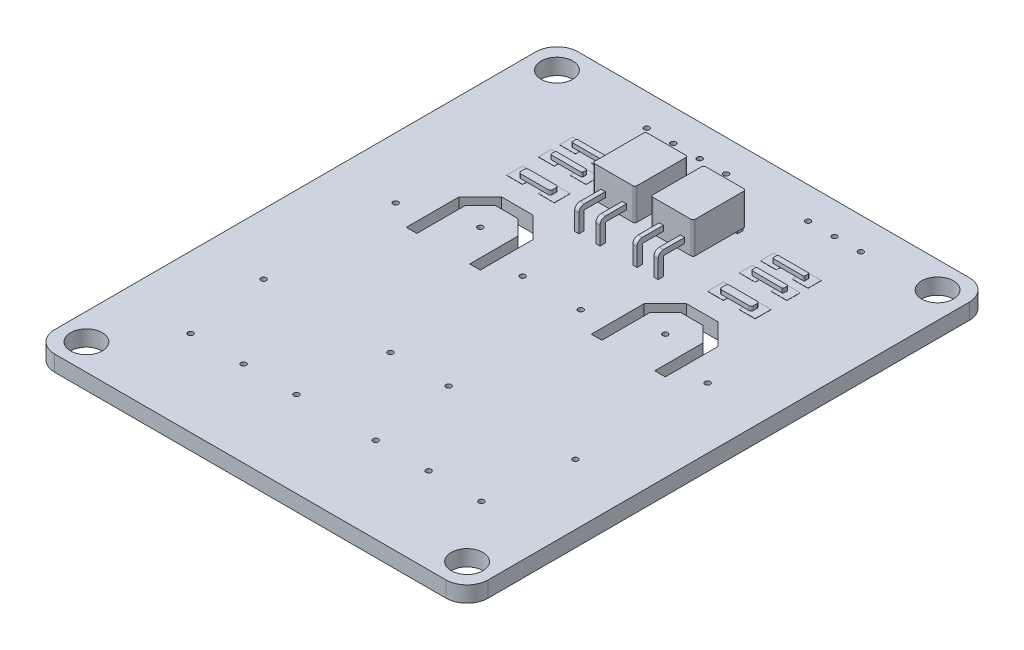
SolidWorks part; units mm, degrees
ref_plane "Ön Düzlem" through (0, 0, 0) normal (0, 0, 1) x (1, 0, 0)
ref_plane "Üst Düzlem" through (0, 0, 0) normal (0, 1, 0) x (1, 0, 0)
ref_plane "Sağ Düzlem" through (0, 0, 0) normal (1, 0, 0) x (0, 0, -1)
sketch "Çizim1" plane through (0, 0, 0) normal (0, 1, 0) x (1, 0, 0)
  line L0 (0, 0) -> (0, 24.75) construction
  line L1 (-18.5, 24.75) -> (18.5, 24.75)
  line L2 (-20.5, 22.75) -> (-20.5, -22.75)
  line L3 (-18.5, -24.75) -> (18.5, -24.75)
  line L4 (20.5, 22.75) -> (20.5, -22.75)
  line L5 (-20.5, 24.75) -> (20.5, -24.75) construction
  line L6 (-20.5, -24.75) -> (20.5, 24.75) construction
  line L7 (0, 24.75) -> (0, 0) construction
  line L8 (0, 0) -> (20.5, 0) construction
  line L9 (-14.75, 24.75) -> (-14.75, -24.75) construction
  line L10 (-20.5, -8.75) -> (20.5, -8.75) construction
  line L11 (-20.5, 3.75) -> (20.5, 3.75) construction
  line L12 (-2.75, 24.75) -> (-2.75, -24.75) construction
  line L13 (-20.5, 5.75) -> (20.5, 5.75) construction
  line L14 (-8.75, 5.75) -> (-8.75, -24.75) construction
  line L15 (-20.5, -16.64) -> (20.5, -16.64) construction
  line L16 (-12.25, 7.25) -> (-10.25, 9.25)
  line L17 (-10.25, 9.25) -> (-7.25, 9.25)
  line L18 (-12.25, 7.25) -> (-12.25, 2.25)
  line L20 (-5.25, 7.25) -> (-5.25, 2.25)
  line L21 (-12.25, 9.25) -> (-5.25, 2.25) construction
  line L22 (-12.25, 2.25) -> (-5.25, 9.25) construction
  line L24 (-6.25, 6.8358) -> (-6.25, 2.25)
  line L26 (-9.8358, 8.25) -> (-7.6642, 8.25)
  line L27 (-11.25, 6.8358) -> (-9.8358, 8.25)
  line L28 (-11.25, 6.8358) -> (-11.25, 2.25)
  line L30 (-12.25, 2.25) -> (-11.25, 2.25)
  line L31 (-6.25, 2.25) -> (-5.25, 2.25)
  line L32 (-7.25, 9.25) -> (-5.25, 7.25)
  line L33 (-7.6642, 8.25) -> (-6.25, 6.8358) construction
  line L34 (-7.25, 9.25) -> (-5.25, 7.25) construction
  line L35 (-7.6642, 8.25) -> (-6.25, 6.8358)
  line L36 (6.25, 2.25) -> (5.25, 2.25)
  line L37 (5.25, 7.25) -> (5.25, 2.25)
  line L38 (6.25, 6.8358) -> (6.25, 2.25)
  line L39 (7.6642, 8.25) -> (6.25, 6.8358)
  line L40 (7.25, 9.25) -> (5.25, 7.25)
  line L41 (9.8358, 8.25) -> (7.6642, 8.25)
  line L42 (10.25, 9.25) -> (7.25, 9.25)
  line L43 (11.25, 6.8358) -> (9.8358, 8.25)
  line L44 (12.25, 7.25) -> (10.25, 9.25)
  line L45 (11.25, 6.8358) -> (11.25, 2.25)
  line L46 (12.25, 7.25) -> (12.25, 2.25)
  line L47 (12.25, 2.25) -> (11.25, 2.25)
  line L48 (-20.5, 21.75) -> (20.5, 21.75) construction
  line L49 (8.75, 5.75) -> (8.75, 24.75) construction
  arc A0 (18.5, -24.75) -> (20.5, -22.75) centre (18.5, -22.75) ccw
  arc A1 (-20.5, -22.75) -> (-18.5, -24.75) centre (-18.5, -22.75) ccw
  arc A2 (18.5, 24.75) -> (20.5, 22.75) centre (18.5, 22.75) cw
  arc A3 (-18.5, 24.75) -> (-20.5, 22.75) centre (-18.5, 22.75) ccw
  circle A4 centre (-18, 22.25) radius 1.5
  circle A5 centre (18, 22.25) radius 1.5
  circle A6 centre (18, -22.25) radius 1.5
  circle A7 centre (-18, -22.25) radius 1.5
  circle A8 centre (-14.75, -8.75) radius 0.25
  circle A10 centre (-2.75, -8.75) radius 0.25
  circle A11 centre (-14.75, 3.75) radius 0.25
  circle A12 centre (-8.75, 5.75) radius 0.25
  circle A13 centre (-2.75, 3.75) radius 0.25
  circle A14 centre (14.75, 3.75) radius 0.25
  circle A15 centre (8.75, 5.75) radius 0.25
  circle A16 centre (2.75, 3.75) radius 0.25
  circle A17 centre (2.75, -8.75) radius 0.25
  circle A18 centre (14.75, -8.75) radius 0.25
  circle A19 centre (-8.75, -16.64) radius 0.25
  circle A20 centre (-3.75, -16.64) radius 0.25
  circle A21 centre (-13.75, -16.64) radius 0.25
  circle A22 centre (3.75, -16.64) radius 0.25
  circle A23 centre (8.75, -16.64) radius 0.25
  circle A24 centre (13.75, -16.64) radius 0.25
  circle A25 centre (-1.5, 21.75) radius 0.25
  circle A26 centre (-4, 21.75) radius 0.25
  circle A27 centre (-6.5, 21.75) radius 0.25
  circle A28 centre (-9, 21.75) radius 0.25
  circle A29 centre (8.75, 21.75) radius 0.25
  circle A30 centre (11.25, 21.75) radius 0.25
  circle A31 centre (6.25, 21.75) radius 0.25
  point P0 (0, 0)
  dimension "D3" = 2
  dimension "D4" = 3
  dimension "D6" = 2.5
  dimension "D9" = 0.5
  dimension "D15" = 0.5
  dimension "D16" = 5
  dimension "D17" = 5
  dimension "D24" = 0.5
  dimension "D25" = 1.5
  dimension "D26" = 2.5
  dimension "D27" = 2.5
  dimension "D28" = 2.5
  dimension "D29" = 0.5
  dimension "D30" = 2.5
  dimension "D31" = 2.5
  dimension "D1" = 41
  dimension "D2" = 49.5
  dimension "D5" = 2.5
  dimension "D7" = 5.75
  dimension "D8" = 16
  dimension "D10" = 12.5
  dimension "D11" = 12
  dimension "D12" = 2
  dimension "D13" = 6
  dimension "D14" = 8.11
  dimension "D18" = 7
  dimension "D19" = 7
  dimension "D21" = 3
  dimension "D20" = 1
extrude "Yükseklik-Ekstrüzyon1" add sketch "Çizim1" along normal blind 1.5
sketch "Çizim2" plane through (0, 1.5, 0) normal (0, 1, 0) x (1, 0, 0)
  line L0 (0, 0) -> (0, 24.75) construction
  line L1 (18.5, 24.75) -> (-18.5, 24.75) construction
  line L2 (-8.75, 9.25) -> (-8.75, 24.75) construction
  line L3 (-7.25, 9.25) -> (-10.25, 9.25) construction
  line L4 (-8.75, 11.25) -> (-20.5, 11.25) construction
  line L5 (-20.5, 22.75) -> (-20.5, -22.75) construction
  line L6 (-8.75, 14.25) -> (-20.5, 14.25) construction
  line L7 (-20.5, 16.25) -> (-8.75, 16.25) construction
  line L8 (-10.25, 9.25) -> (-10.25, 16.25) construction
  line L9 (8.75, 12.75) -> (7.25, 12.75)
  line L10 (-8.75, 11.25) -> (-7.25, 11.25)
  line L11 (-8.75, 11.25) -> (-8.75, 12.75)
  line L12 (-8.75, 12.75) -> (-7.25, 12.75)
  line L13 (-7.25, 11.25) -> (-7.25, 12.75)
  line L14 (-10.25, 11.25) -> (-11.75, 11.25)
  line L15 (-10.25, 11.25) -> (-10.25, 12.75)
  line L16 (-10.25, 12.75) -> (-11.75, 12.75)
  line L17 (-11.75, 11.25) -> (-11.75, 12.75)
  line L18 (-8.75, 14.25) -> (-7.25, 14.25)
  line L19 (-8.75, 14.25) -> (-8.75, 15.5)
  line L20 (-8.75, 15.5) -> (-7.25, 15.5)
  line L21 (-7.25, 14.25) -> (-7.25, 15.5)
  line L22 (-10.25, 14.25) -> (-11.75, 14.25)
  line L23 (-10.25, 14.25) -> (-10.25, 15.5)
  line L24 (-10.25, 15.5) -> (-11.75, 15.5)
  line L25 (-11.75, 14.25) -> (-11.75, 15.5)
  line L26 (-8.75, 16.25) -> (-7.25, 16.25)
  line L27 (-8.75, 16.25) -> (-8.75, 17.5)
  line L28 (-8.75, 17.5) -> (-7.25, 17.5)
  line L29 (-7.25, 16.25) -> (-7.25, 17.5)
  line L30 (-10.25, 16.25) -> (-11.75, 16.25)
  line L31 (-10.25, 16.25) -> (-10.25, 17.5)
  line L32 (-10.25, 17.5) -> (-11.75, 17.5)
  line L33 (-11.75, 16.25) -> (-11.75, 17.5)
  line L34 (7.25, 11.25) -> (7.25, 12.75)
  line L35 (8.75, 11.25) -> (7.25, 11.25)
  line L36 (8.75, 11.25) -> (8.75, 12.75)
  line L37 (10.25, 12.75) -> (11.75, 12.75)
  line L38 (11.75, 11.25) -> (11.75, 12.75)
  line L39 (10.25, 11.25) -> (11.75, 11.25)
  line L40 (10.25, 11.25) -> (10.25, 12.75)
  line L41 (8.75, 15.5) -> (7.25, 15.5)
  line L42 (7.25, 14.25) -> (7.25, 15.5)
  line L43 (8.75, 14.25) -> (7.25, 14.25)
  line L44 (8.75, 14.25) -> (8.75, 15.5)
  line L45 (10.25, 15.5) -> (11.75, 15.5)
  line L46 (11.75, 14.25) -> (11.75, 15.5)
  line L47 (10.25, 14.25) -> (11.75, 14.25)
  line L48 (10.25, 14.25) -> (10.25, 15.5)
  line L49 (8.75, 17.5) -> (7.25, 17.5)
  line L50 (7.25, 16.25) -> (7.25, 17.5)
  line L51 (8.75, 16.25) -> (7.25, 16.25)
  line L52 (8.75, 16.25) -> (8.75, 17.5)
  line L53 (10.25, 17.5) -> (11.75, 17.5)
  line L54 (11.75, 16.25) -> (11.75, 17.5)
  line L55 (10.25, 16.25) -> (11.75, 16.25)
  line L56 (10.25, 16.25) -> (10.25, 17.5)
  dimension "D1" = 2
  dimension "D2" = 3
  dimension "D3" = 2
  dimension "D4" = 1.5
  dimension "D5" = 1.5
  dimension "D6" = 1.5
  dimension "D7" = 1.5
  dimension "D8" = 1.25
  dimension "D9" = 1.5
  dimension "D10" = 1.25
  dimension "D11" = 1.5
  dimension "D12" = 1.25
  dimension "D13" = 1.25
  dimension "D14" = 1.5
  dimension "D15" = 1.5
extrude "Yükseklik-Ekstrüzyon2" add sketch "Çizim2" along normal blind 0.02
sketch "Çizim3" plane through (0, 1.52, 0) normal (0, 1, 0) x (1, 0, 0)
  line L0 (-11.75, 12) -> (-7.25, 12) construction
  line L1 (-11.75, 12.75) -> (-11.75, 11.25) construction
  line L2 (-7.25, 11.25) -> (-7.25, 12.75) construction
  line L3 (-7.25, 12) -> (-9.5, 12) construction
  line L4 (-9.5, 12) -> (-9.5, 16.3146) construction
  line L5 (-11.75, 14.875) -> (-7.25, 14.875) construction
  line L6 (-11.75, 15.5) -> (-11.75, 14.25) construction
  line L7 (-7.25, 14.25) -> (-7.25, 15.5) construction
  line L8 (-11.75, 16.875) -> (-7.25, 16.875) construction
  line L9 (-11.75, 17.5) -> (-11.75, 16.25) construction
  line L10 (-7.25, 16.25) -> (-7.25, 17.5) construction
  line L11 (0, 0) -> (0, 25.4202) construction
  line L12 (-10.9, 17.125) -> (-8.1, 17.125)
  line L13 (-11, 17.025) -> (-11, 16.725)
  line L14 (-10.9, 16.625) -> (-8.1, 16.625)
  line L15 (-8, 17.025) -> (-8, 16.725)
  line L16 (-11, 17.125) -> (-8, 16.625) construction
  line L17 (-11, 16.625) -> (-8, 17.125) construction
  line L18 (-10.9, 15.125) -> (-8.1, 15.125)
  line L19 (-11, 15.025) -> (-11, 14.725)
  line L20 (-10.9, 14.625) -> (-8.1, 14.625)
  line L21 (-8, 15.025) -> (-8, 14.725)
  line L22 (-11, 15.125) -> (-8, 14.625) construction
  line L23 (-11, 14.625) -> (-8, 15.125) construction
  line L24 (-10.8, 12.375) -> (-8.2, 12.375)
  line L25 (-11, 12.175) -> (-11, 11.825)
  line L26 (-10.8, 11.625) -> (-8.2, 11.625)
  line L27 (-8, 12.175) -> (-8, 11.825)
  line L28 (-11, 12.375) -> (-8, 11.625) construction
  line L29 (-11, 11.625) -> (-8, 12.375) construction
  line L30 (10.9, 16.625) -> (8.1, 16.625)
  line L31 (8, 17.025) -> (8, 16.725)
  line L32 (10.9, 17.125) -> (8.1, 17.125)
  line L33 (11, 17.025) -> (11, 16.725)
  line L34 (10.9, 14.625) -> (8.1, 14.625)
  line L35 (8, 15.025) -> (8, 14.725)
  line L36 (10.9, 15.125) -> (8.1, 15.125)
  line L37 (11, 15.025) -> (11, 14.725)
  line L38 (10.8, 11.625) -> (8.2, 11.625)
  line L39 (8, 12.175) -> (8, 11.825)
  line L40 (10.8, 12.375) -> (8.2, 12.375)
  line L41 (11, 12.175) -> (11, 11.825)
  arc A0 (-8.1, 14.625) -> (-8, 14.725) centre (-8.1, 14.725) ccw
  arc A1 (-8.1, 15.125) -> (-8, 15.025) centre (-8.1, 15.025) cw
  arc A2 (-11, 14.725) -> (-10.9, 14.625) centre (-10.9, 14.725) ccw
  arc A3 (-10.9, 15.125) -> (-11, 15.025) centre (-10.9, 15.025) ccw
  arc A4 (-8.1, 16.625) -> (-8, 16.725) centre (-8.1, 16.725) ccw
  arc A5 (-8.1, 17.125) -> (-8, 17.025) centre (-8.1, 17.025) cw
  arc A6 (-11, 16.725) -> (-10.9, 16.625) centre (-10.9, 16.725) ccw
  arc A7 (-10.9, 17.125) -> (-11, 17.025) centre (-10.9, 17.025) ccw
  arc A8 (-8.2, 11.625) -> (-8, 11.825) centre (-8.2, 11.825) ccw
  arc A9 (-8.2, 12.375) -> (-8, 12.175) centre (-8.2, 12.175) cw
  arc A10 (-11, 11.825) -> (-10.8, 11.625) centre (-10.8, 11.825) ccw
  arc A11 (-10.8, 12.375) -> (-11, 12.175) centre (-10.8, 12.175) ccw
  arc A12 (8.1, 16.625) -> (8, 16.725) centre (8.1, 16.725) cw
  arc A13 (8.1, 17.125) -> (8, 17.025) centre (8.1, 17.025) ccw
  arc A14 (11, 16.725) -> (10.9, 16.625) centre (10.9, 16.725) cw
  arc A15 (10.9, 17.125) -> (11, 17.025) centre (10.9, 17.025) cw
  arc A16 (8.1, 14.625) -> (8, 14.725) centre (8.1, 14.725) cw
  arc A17 (8.1, 15.125) -> (8, 15.025) centre (8.1, 15.025) ccw
  arc A18 (11, 14.725) -> (10.9, 14.625) centre (10.9, 14.725) cw
  arc A19 (10.9, 15.125) -> (11, 15.025) centre (10.9, 15.025) cw
  arc A20 (8.2, 11.625) -> (8, 11.825) centre (8.2, 11.825) cw
  arc A21 (8.2, 12.375) -> (8, 12.175) centre (8.2, 12.175) ccw
  arc A22 (11, 11.825) -> (10.8, 11.625) centre (10.8, 11.825) cw
  arc A23 (10.8, 12.375) -> (11, 12.175) centre (10.8, 12.175) cw
  point P20 (-9.5, 16.875)
  point P25 (-9.5, 14.875)
  dimension "D5" = 0.1
  dimension "D6" = 0.2
  dimension "D1" = 0.5
  dimension "D2" = 3
  dimension "D3" = 0.5
  dimension "D4" = 0.75
extrude "Yükseklik-Ekstrüzyon3" add sketch "Çizim3" along normal blind 0.4
ref_plane "Düzlem2" through (0, 2.5, 0) normal (0, 1, 0) x (1, 0, 0)
sketch "Çizim5" plane through (0, 2.5, 0) normal (0, 1, 0) x (1, 0, 0)
  line L0 (0, 0) -> (0, 27.9522) construction
  line L1 (-11, 14.875) -> (0, 14.875) construction
  line L2 (-11, 15.025) -> (-11, 14.725) construction
  line L3 (4.55, 12.375) -> (0.95, 12.375)
  line L4 (-4.55, 17.375) -> (-0.95, 17.375)
  line L5 (-4.75, 17.175) -> (-4.75, 12.575)
  line L6 (-4.55, 12.375) -> (-0.95, 12.375)
  line L7 (-0.75, 17.175) -> (-0.75, 12.575)
  line L8 (-4.75, 17.375) -> (-0.75, 12.375) construction
  line L9 (-4.75, 12.375) -> (-0.75, 17.375) construction
  line L10 (0.75, 17.175) -> (0.75, 12.575)
  line L11 (4.55, 17.375) -> (0.95, 17.375)
  line L12 (4.75, 17.175) -> (4.75, 12.575)
  arc A0 (-0.95, 12.375) -> (-0.75, 12.575) centre (-0.95, 12.575) ccw
  arc A1 (-4.75, 12.575) -> (-4.55, 12.375) centre (-4.55, 12.575) ccw
  arc A2 (-0.95, 17.375) -> (-0.75, 17.175) centre (-0.95, 17.175) cw
  arc A3 (-4.55, 17.375) -> (-4.75, 17.175) centre (-4.55, 17.175) ccw
  arc A4 (0.95, 12.375) -> (0.75, 12.575) centre (0.95, 12.575) cw
  arc A5 (0.95, 17.375) -> (0.75, 17.175) centre (0.95, 17.175) ccw
  arc A6 (4.75, 12.575) -> (4.55, 12.375) centre (4.55, 12.575) cw
  arc A7 (4.55, 17.375) -> (4.75, 17.175) centre (4.55, 17.175) cw
  point P7 (-2.75, 14.875)
  dimension "D4" = 0.2
  dimension "D1" = 5
  dimension "D2" = 4
  dimension "D3" = 0.75
extrude "Yükseklik-Ekstrüzyon4" add sketch "Çizim5" along normal blind 3 separate body
ref_plane "Düzlem3" through (-3.75, 0, 0) normal (-1, 0, 0) x (0, 0, 1)
sketch "Çizim8" plane through (-3.75, 0, 0) normal (-1, 0, 0) x (0, 0, 1)
  line L0 (-14.875, 2.5) -> (-14.875, 0) construction
  line L1 (-17.175, 2.5) -> (-12.575, 2.5) construction
  line L2 (-22.75, 0) -> (22.75, 0) construction
  line L3 (-17.375, 3.2109) -> (-10.375, 3.2109)
  line L5 (-17.875, 0.7988) -> (-17.875, 3.2109)
  line L6 (-17.375, 3.7109) -> (-10.375, 3.7109)
  line L7 (-9.875, 0.7988) -> (-9.875, 3.2109)
  line L8 (-10.375, 0.7988) -> (-9.875, 0.7988)
  line L9 (-17.875, 3.7109) -> (-14.875, 0) construction
  line L10 (-10.375, 0.7988) -> (-10.375, 3.2109)
  line L12 (-17.375, 0.7988) -> (-17.375, 3.2109)
  line L13 (-17.875, 0.7988) -> (-17.375, 0.7988)
  line L14 (-17.875, -3.7109) -> (-17.875, 3.7109) construction
  line L15 (-17.375, -3.2109) -> (-17.375, 3.2109) construction
  line L16 (-14.875, 0) -> (-9.875, 3.7109) construction
  line L17 (-17.875, 3.7109) -> (-9.875, 3.7109) construction
  line L18 (-10.375, -3.2109) -> (-10.375, 3.2109) construction
  line L19 (-9.875, -3.7109) -> (-9.875, 3.7109) construction
  line L21 (-17.375, -3.2109) -> (-10.375, -3.2109) construction
  line L22 (-17.875, -3.7109) -> (-9.875, -3.7109) construction
  arc A0 (-10.375, 3.7109) -> (-9.875, 3.2109) centre (-10.375, 3.2109) cw
  arc A1 (-17.875, 3.2109) -> (-17.375, 3.7109) centre (-17.375, 3.2109) cw
  dimension "D3" = 0.5
  dimension "D1" = 8
  dimension "D2" = 0.5
extrude "Yükseklik-Ekstrüzyon5" add sketch "Çizim8" along normal blind 0.2 and the other way blind 0.2
ref_plane "Düzlem4" through (-1.75, 0, 0) normal (1, 0, 0) x (0, 0, -1)
sketch "Çizim9" plane through (-1.75, 0, 0) normal (1, 0, 0) x (0, 0, -1)
  line L0 (14.875, 2.5) -> (14.875, 0) construction
  line L1 (12.575, 2.5) -> (17.175, 2.5) construction
  line L2 (-22.75, 0) -> (22.75, 0) construction
  line L3 (10.3784, 0.5594) -> (10.3784, 3.2109)
  line L5 (9.8784, 0.5594) -> (9.8784, 3.2109)
  line L6 (10.3784, 3.7109) -> (17.3716, 3.7109)
  line L7 (17.8716, 0.5594) -> (17.8716, 3.2109)
  line L9 (9.8784, 3.7109) -> (14.875, 0) construction
  line L10 (10.3784, 3.2109) -> (17.3716, 3.2109)
  line L11 (17.3716, 0.5594) -> (17.3716, 3.2109)
  line L13 (9.8784, 3.7109) -> (17.8716, 3.7109) construction
  line L14 (17.8716, -3.7109) -> (17.8716, 3.7109) construction
  line L15 (9.8784, -3.7109) -> (9.8784, 3.7109) construction
  line L16 (9.8784, 0.5594) -> (10.3784, 0.5594)
  line L17 (10.3784, -3.2109) -> (10.3784, 3.2109) construction
  line L18 (17.3716, 0.5594) -> (17.8716, 0.5594)
  line L19 (17.3716, -3.2109) -> (17.3716, 3.2109) construction
  line L20 (14.875, 0) -> (17.8716, 3.7109) construction
  line L22 (10.3784, -3.2109) -> (17.3716, -3.2109) construction
  line L24 (9.8784, -3.7109) -> (17.8716, -3.7109) construction
  arc A0 (17.3716, 3.7109) -> (17.8716, 3.2109) centre (17.3716, 3.2109) cw
  arc A1 (9.8784, 3.2109) -> (10.3784, 3.7109) centre (10.3784, 3.2109) cw
  dimension "D2" = 0.5
  dimension "D1" = 0.5
extrude "Yükseklik-Ekstrüzyon6" add sketch "Çizim9" along normal blind 0.2 and the other way blind 0.2
ref_plane "Düzlem5" through (3.75, 0, 0) normal (1, 0, 0) x (0, 0, -1)
sketch "Çizim10" plane through (3.75, 0, 0) normal (1, 0, 0) x (0, 0, -1)
  line L0 (14.875, 2.5) -> (14.875, 0) construction
  line L1 (12.575, 2.5) -> (17.175, 2.5) construction
  line L2 (-22.75, 0) -> (22.75, 0) construction
  line L3 (10.375, 0.6252) -> (10.375, 3.2128)
  line L5 (9.875, 0.6252) -> (9.875, 3.2128)
  line L6 (10.375, 3.7128) -> (17.375, 3.7128)
  line L7 (17.875, 0.6252) -> (17.875, 3.2128)
  line L9 (9.875, 3.7128) -> (14.875, 0) construction
  line L10 (10.375, 3.2128) -> (17.375, 3.2128)
  line L11 (17.375, 0.6252) -> (17.375, 3.2128)
  line L13 (9.875, 3.7128) -> (17.875, 3.7128) construction
  line L14 (17.875, -3.7128) -> (17.875, 3.7128) construction
  line L15 (9.875, -3.7128) -> (9.875, 3.7128) construction
  line L16 (9.875, 0.6252) -> (10.375, 0.6252)
  line L17 (10.375, -3.2128) -> (10.375, 3.2128) construction
  line L18 (14.875, 0) -> (17.875, 3.7128) construction
  line L19 (17.375, 0.6252) -> (17.875, 0.6252)
  line L20 (17.375, -3.2128) -> (17.375, 3.2128) construction
  line L21 (9.875, -3.7128) -> (17.875, -3.7128) construction
  line L22 (10.375, -3.2128) -> (17.375, -3.2128) construction
  arc A0 (17.375, 3.7128) -> (17.875, 3.2128) centre (17.375, 3.2128) cw
  arc A1 (9.875, 3.2128) -> (10.375, 3.7128) centre (10.375, 3.2128) cw
  dimension "D2" = 0.5
  dimension "D1" = 0.5
extrude "Yükseklik-Ekstrüzyon7" add sketch "Çizim10" along normal blind 0.2 and the other way blind 0.2
ref_plane "Düzlem6" through (1.75, 0, 0) normal (-1, 0, 0) x (0, 0, 1)
sketch "Çizim11" plane through (1.75, 0, 0) normal (-1, 0, 0) x (0, 0, 1)
  line L0 (-14.875, 2.5) -> (-14.875, 0) construction
  line L1 (-17.175, 2.5) -> (-12.575, 2.5) construction
  line L2 (-22.75, 0) -> (22.75, 0) construction
  line L3 (-17.375, 0.556) -> (-17.375, 3.2109)
  line L5 (-17.875, 0.556) -> (-17.875, 3.2109)
  line L6 (-17.375, 3.7109) -> (-10.375, 3.7109)
  line L7 (-9.875, 0.556) -> (-9.875, 3.2109)
  line L8 (-10.375, 0.556) -> (-9.875, 0.556)
  line L9 (-17.875, 3.7109) -> (-14.875, 0) construction
  line L10 (-17.375, 3.2109) -> (-10.375, 3.2109)
  line L11 (-10.375, 0.556) -> (-10.375, 3.2109)
  line L13 (-17.875, 3.7109) -> (-9.875, 3.7109) construction
  line L14 (-9.875, -3.7109) -> (-9.875, 3.7109) construction
  line L15 (-17.875, -3.7109) -> (-17.875, 3.7109) construction
  line L16 (-17.875, 0.556) -> (-17.375, 0.556)
  line L17 (-17.375, -3.2109) -> (-17.375, 3.2109) construction
  line L18 (-14.875, 0) -> (-9.875, 3.7109) construction
  line L20 (-10.375, -3.2109) -> (-10.375, 3.2109) construction
  line L21 (-17.875, -3.7109) -> (-9.875, -3.7109) construction
  line L22 (-17.375, -3.2109) -> (-10.375, -3.2109) construction
  arc A0 (-10.375, 3.7109) -> (-9.875, 3.2109) centre (-10.375, 3.2109) cw
  arc A1 (-17.875, 3.2109) -> (-17.375, 3.7109) centre (-17.375, 3.2109) cw
  dimension "D2" = 0.5
  dimension "D1" = 0.5
extrude "Yükseklik-Ekstrüzyon8" add sketch "Çizim11" along normal blind 0.2 and the other way blind 0.2
